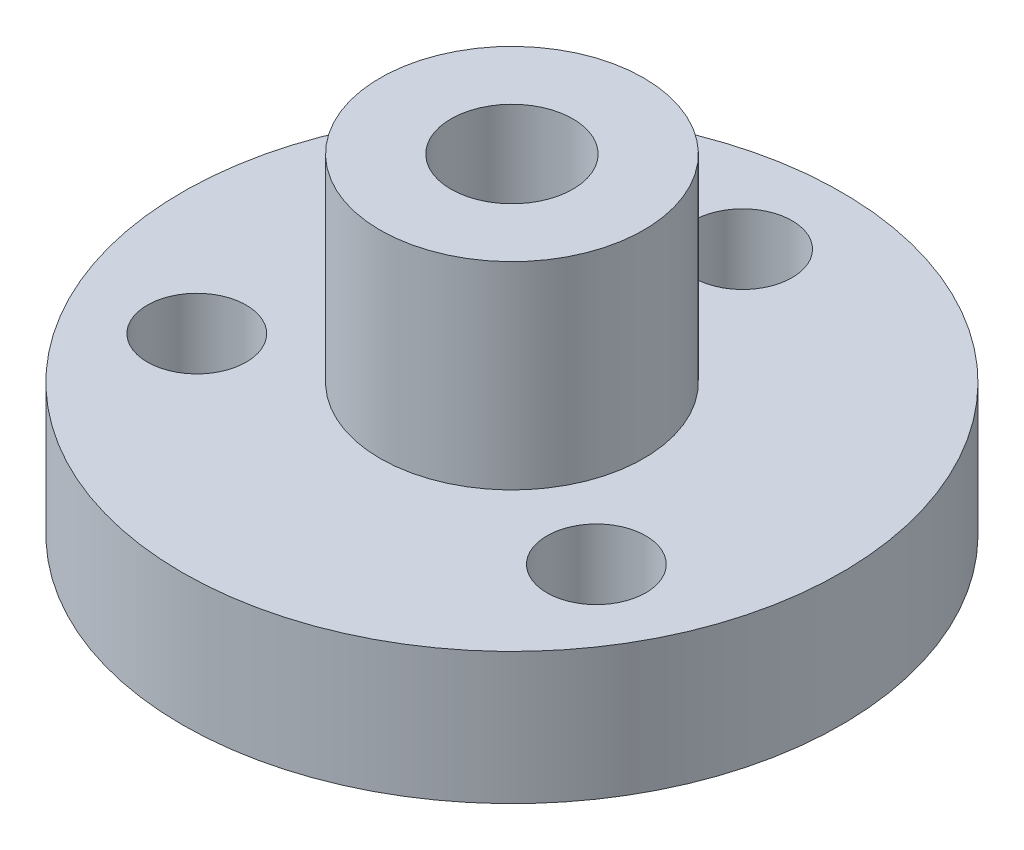
SolidWorks part; units mm, degrees
material "6063-T4"
ref_plane "Front Plane" through (0, 0, 0) normal (0, 0, 1) x (1, 0, 0)
ref_plane "Top Plane" through (0, 0, 0) normal (0, 1, 0) x (1, 0, 0)
ref_plane "Right Plane" through (0, 0, 0) normal (1, 0, 0) x (0, 0, -1)
sketch "Sketch1" plane through (0, 0, 0) normal (0, 1, 0) x (1, 0, 0)
  circle A0 centre (0, 0) radius 10
  dimension "D1" = 20
extrude "Boss-Extrude1" add sketch "Sketch1" along normal blind 4
sketch "Sketch2" plane through (0, 4, 0) normal (0, 1, 0) x (1, 0, 0)
  circle A0 centre (0, 0) radius 4
  dimension "D1" = 8
extrude "Boss-Extrude2" add sketch "Sketch2" along normal blind 6
sketch "Sketch3" plane through (0, 10, 0) normal (0, 1, 0) x (1, 0, 0)
  circle A0 centre (0, 0) radius 1.85
  dimension "D1" = 3.7
extrude "Cut-Extrude1" cut sketch "Sketch3" against normal through all
sketch "Sketch4" plane through (0, 4, 0) normal (0, 1, 0) x (1, 0, 0)
  circle A0 centre (0, 0) radius 7 construction
  circle A2 centre (0, 7) radius 1.5
  dimension "D1" = 14
  dimension "D2" = 3
extrude "Cut-Extrude2" cut sketch "Sketch4" against normal through all
pattern_circular "CirPattern1" count 3 over 360 about axis through (0, 0, 0) along (0, 1, 0) of "Cut-Extrude2"
